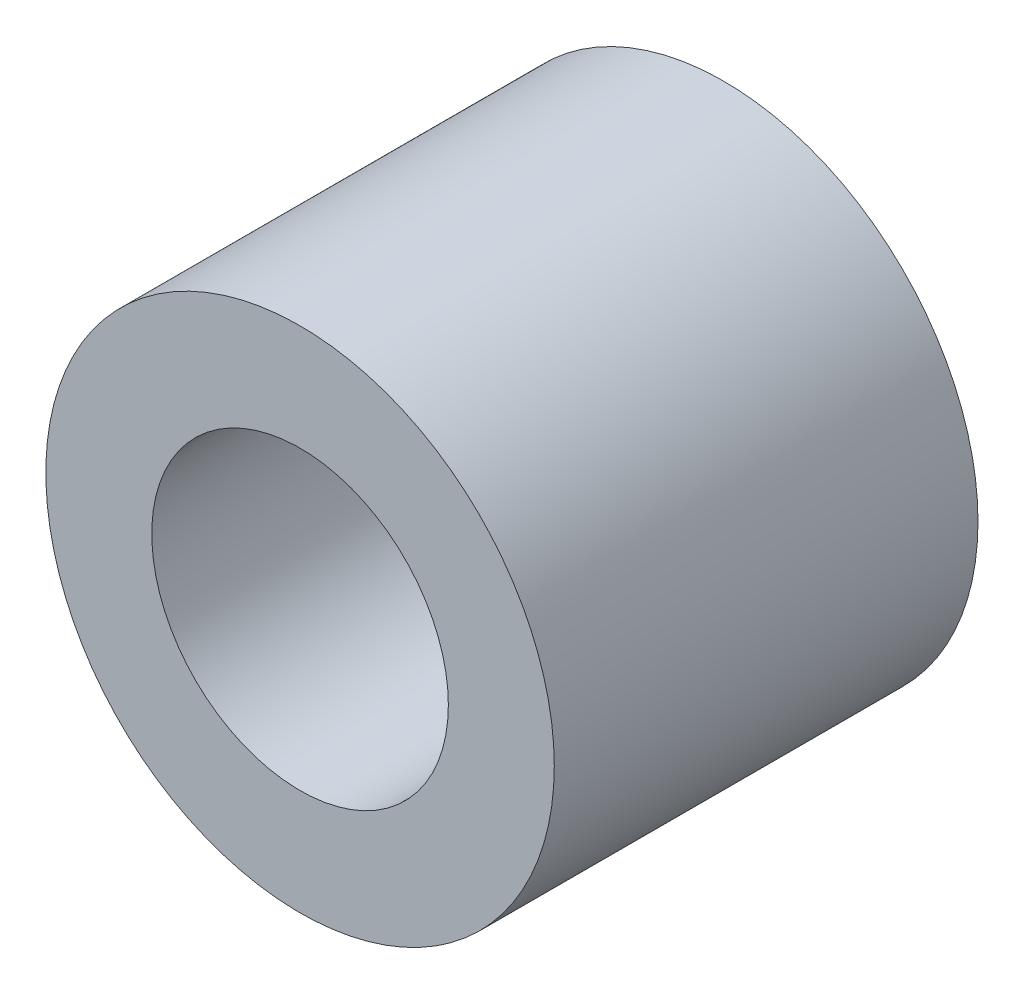
SolidWorks part; units mm, degrees
ref_plane "前视基准面" through (0, 0, 0) normal (0, 0, 1) x (1, 0, 0)
ref_plane "上视基准面" through (0, 0, 0) normal (0, 1, 0) x (1, 0, 0)
ref_plane "右视基准面" through (0, 0, 0) normal (1, 0, 0) x (0, 0, -1)
sketch "草图1" plane through (0, 0, 0) normal (0, 0, 1) x (1, 0, 0)
  circle A0 centre (0, 0) radius 3.5
  circle A1 centre (0, 0) radius 6
extrude "凸台-拉伸1" add sketch "草图1" along normal blind 10
